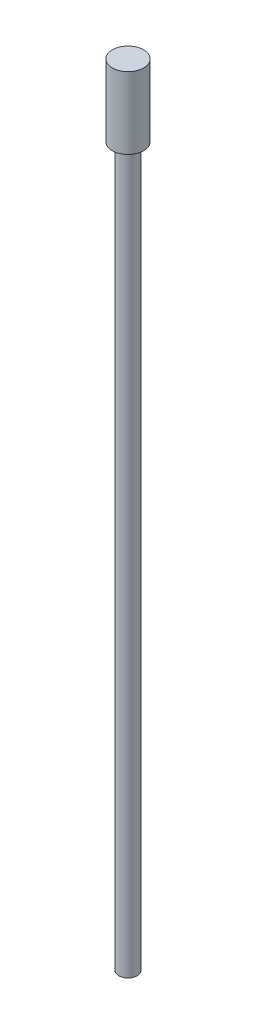
SolidWorks part; units mm, degrees
ref_plane "Front Plane" through (0, 0, 0) normal (0, 0, 1) x (1, 0, 0)
ref_plane "Top Plane" through (0, 0, 0) normal (0, 1, 0) x (1, 0, 0)
ref_plane "Right Plane" through (0, 0, 0) normal (1, 0, 0) x (0, 0, -1)
sketch "Sketch1" plane through (0, 0, 0) normal (0, 1, 0) x (1, 0, 0)
  circle A0 centre (0, 0) radius 2.55
  dimension "D1" = 5.1
extrude "Boss-Extrude1" add sketch "Sketch1" along normal blind 200
sketch "Sketch2" plane through (0, 200, 0) normal (0, 1, 0) x (1, 0, 0)
  circle A0 centre (0, 0) radius 4.375
  dimension "D1" = 8.75
extrude "Boss-Extrude2" add sketch "Sketch2" along normal blind 20
